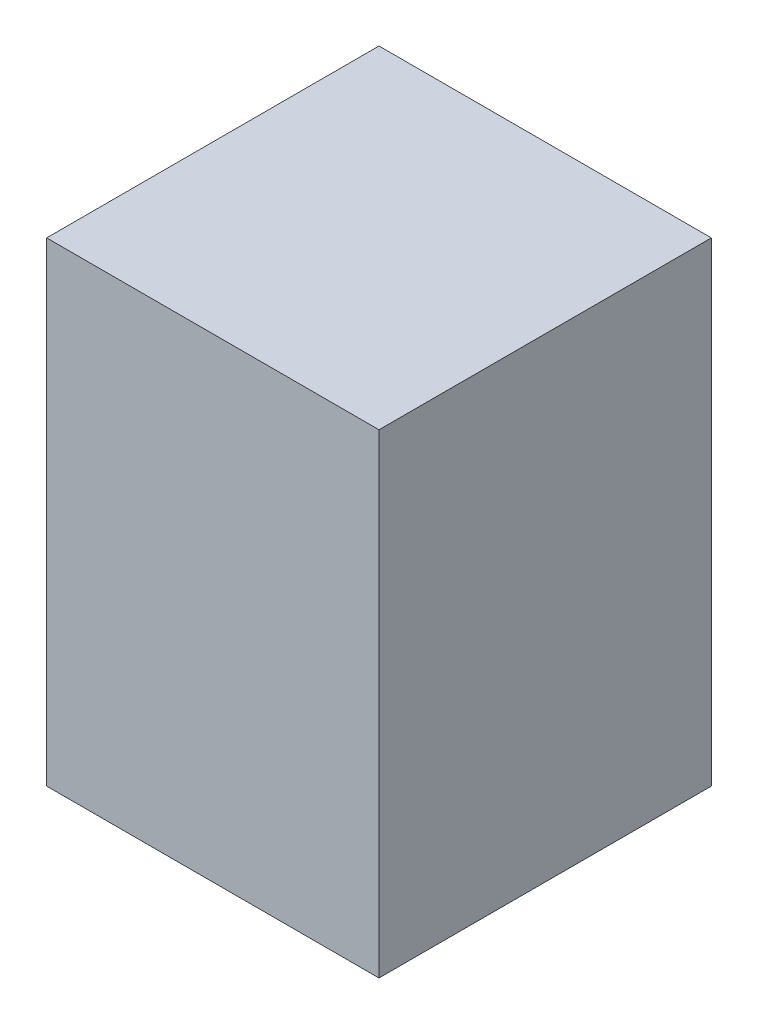
SolidWorks part; units mm, degrees
ref_plane "前基準面" through (0, 0, 0) normal (0, 0, 1) x (1, 0, 0)
ref_plane "上基準面" through (0, 0, 0) normal (0, 1, 0) x (1, 0, 0)
ref_plane "右基準面" through (0, 0, 0) normal (1, 0, 0) x (0, 0, -1)
sketch "草圖1" plane through (0, 0, 0) normal (0, 0, 1) x (1, 0, 0)
  line L1 (-14863.8393, 9281.25) -> (-14513.8393, 9281.25)
  line L2 (-14863.8393, 9281.25) -> (-14863.8393, 8781.25)
  line L3 (-14863.8393, 8781.25) -> (-14513.8393, 8781.25)
  line L4 (-14513.8393, 9281.25) -> (-14513.8393, 8781.25)
  dimension "D1" = 500
  dimension "D2" = 350
extrude "填料-伸長1" add sketch "草圖1" along normal blind 350
